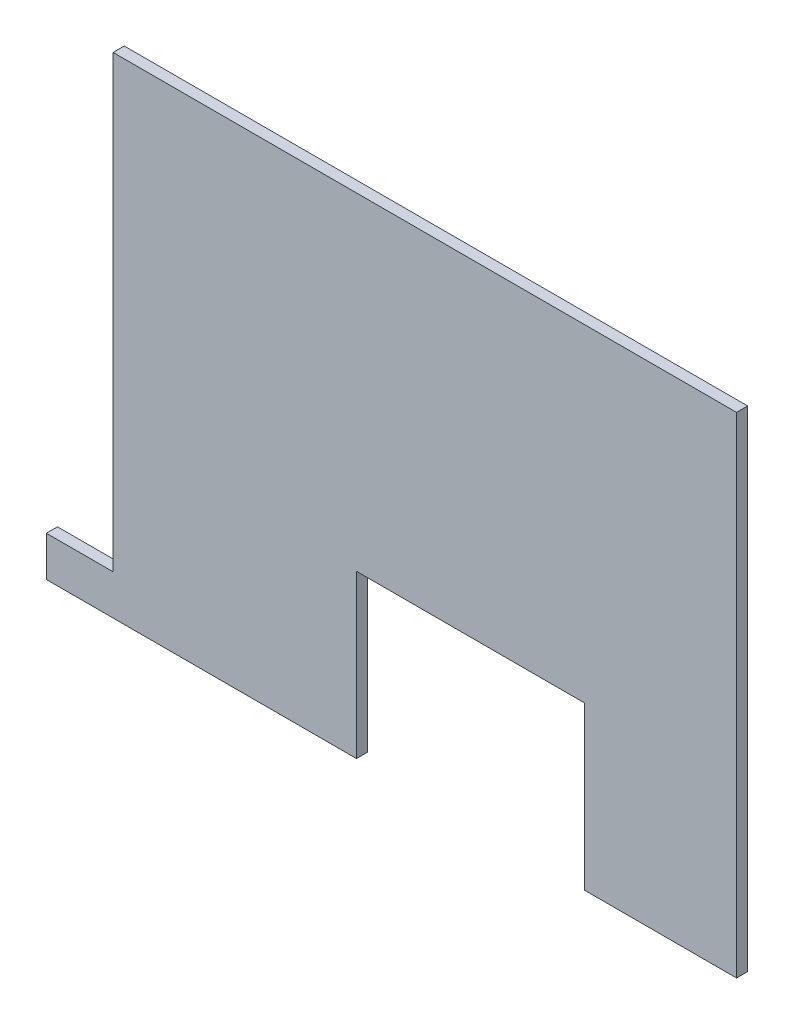
SolidWorks part; units mm, degrees
ref_plane "Front Plane" through (0, 0, 0) normal (0, 0, 1) x (1, 0, 0)
ref_plane "Top Plane" through (0, 0, 0) normal (0, 1, 0) x (1, 0, 0)
ref_plane "Right Plane" through (0, 0, 0) normal (1, 0, 0) x (0, 0, -1)
sketch "Sketch1" plane through (0, 0, 0) normal (0, 0, 1) x (1, 0, 0)
  line L1 (-140, -110) -> (140, -110)
  line L2 (-140, -110) -> (-140, 110)
  line L3 (-140, 110) -> (140, 110)
  line L4 (140, -110) -> (140, 110)
  line L5 (0, 110) -> (0, -110) construction
  line L6 (-140, 0) -> (140, 0) construction
  line L7 (-140, -110) -> (-170, -110)
  line L8 (-140, -110) -> (-140, -92)
  line L9 (-140, -92) -> (-170, -92)
  line L10 (-170, -110) -> (-170, -92)
  line L11 (-30.6982, -110) -> (71.6105, -110)
  line L12 (-30.6982, -110) -> (-30.6982, -37.1653)
  line L13 (-30.6982, -37.1653) -> (71.6105, -37.1653)
  line L14 (71.6105, -110) -> (71.6105, -37.1653)
  point P0 (0, 0)
  dimension "D1" = 220
  dimension "D2" = 280
  dimension "D3" = 18
  dimension "D4" = 30
extrude "Boss-Extrude1" add sketch "Sketch1" along normal blind 5 contours L1 L4 L3 L2 | L10 L7 L2 L9
